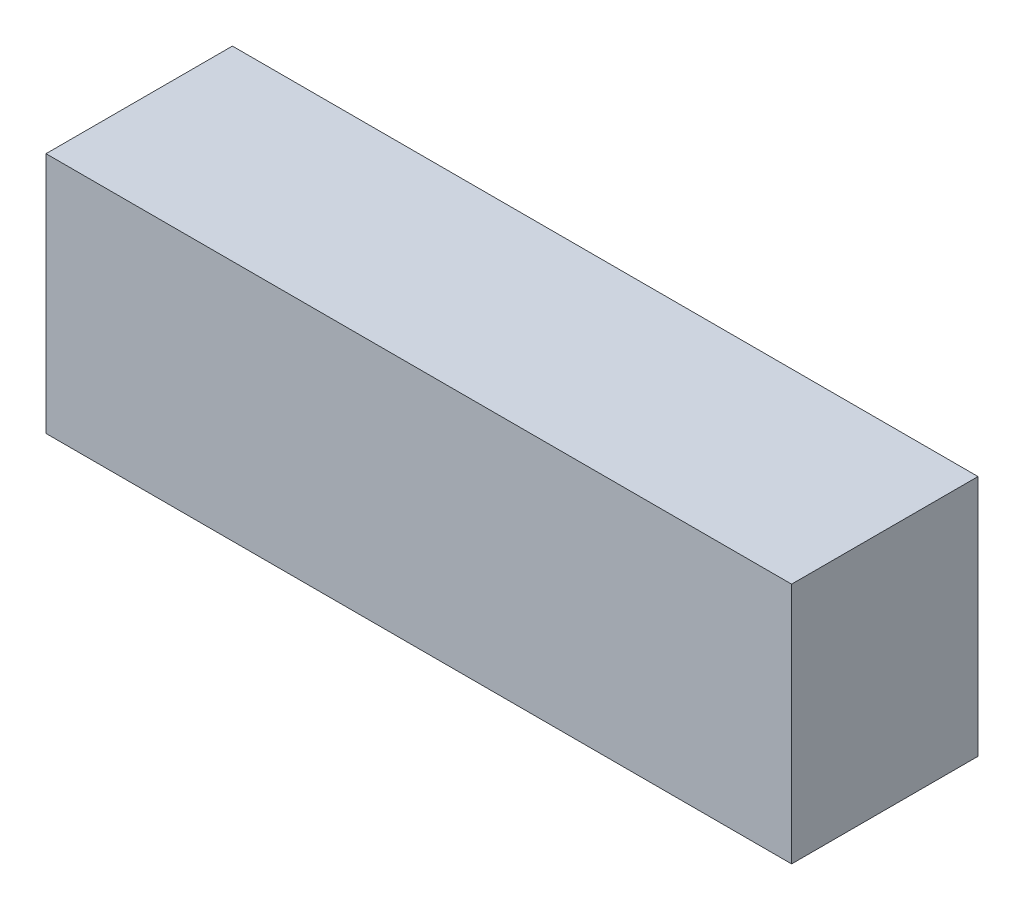
SolidWorks part; units mm, degrees
ref_plane "Front Plane" through (0, 0, 0) normal (0, 0, 1) x (1, 0, 0)
ref_plane "Top Plane" through (0, 0, 0) normal (0, 1, 0) x (1, 0, 0)
ref_plane "Right Plane" through (0, 0, 0) normal (1, 0, 0) x (0, 0, -1)
sketch "Sketch1" plane through (0, 0, 0) normal (0, 0, 1) x (1, 0, 0)
  line L1 (0, 0) -> (40, 0)
  line L2 (0, 0) -> (0, 13)
  line L3 (0, 13) -> (40, 13)
  line L4 (40, 0) -> (40, 13)
extrude "Boss-Extrude1" add sketch "Sketch1" against normal blind 10
